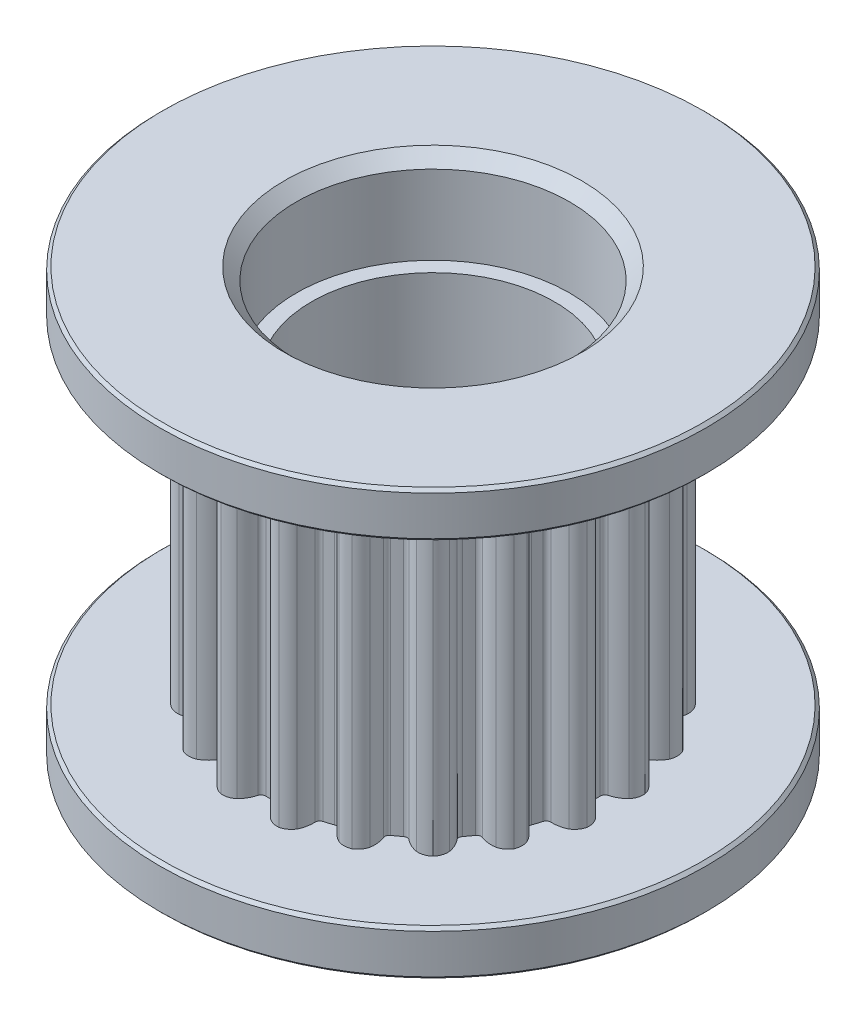
SolidWorks part; units mm, degrees
material "6061 Alloy"
ref_plane "Front Plane" through (0, 0, 0) normal (0, 0, 1) x (1, 0, 0)
ref_plane "Top Plane" through (0, 0, 0) normal (0, 1, 0) x (1, 0, 0)
ref_plane "Right Plane" through (0, 0, 0) normal (1, 0, 0) x (0, 0, -1)
sketch "Body Sketch" plane through (0, 0, 0) normal (0, 0, 1) x (1, 0, 0)
  line L0 (6.11, -5.5) -> (6.11, 5.5)
  line L1 (6.11, 5.5) -> (9, 5.5)
  line L2 (9, 5.5) -> (9, 7)
  line L3 (9, 7) -> (4.5, 7)
  line L4 (4.5, 7) -> (4.5, 4)
  line L5 (4.5, 4) -> (4, 4)
  line L6 (4, 4) -> (4, -4)
  line L7 (4, -4) -> (4.5, -4)
  line L8 (4.5, -4) -> (4.5, -7)
  line L9 (4.5, -7) -> (9, -7)
  line L10 (9, -7) -> (9, -5.5)
  line L11 (9, -5.5) -> (6.11, -5.5)
  line L12 (0, 0) -> (4, 0) construction
  line L13 (0, 7) -> (0, -7) construction
  dimension "BearingOD" = 9
  dimension "Height" = 14
  dimension "FlangeHeight" = 1.5
  dimension "BearingHeight" = 3
  dimension "BearingRestDiaControl" = 0.5
  dimension "RefBodyInnerDiameter" = 8
  dimension "FlangeDiaControl" = 4.5
  dimension "RefFlangeDia" = 18
  dimension "BeltPathDiaControl" = 1.61
  dimension "RefBeltPathDia" = 12.22
revolve "Body" add sketch "Body Sketch" angle 360 about L13
sketch "GT2 Profile Sketch" plane through (0, 0, 0) normal (0, 1, 0) x (1, 0, 0)
  line L1 (0, -6.11) -> (0, -5.36) construction
  line L2 (-0.9955, -6.0283) -> (-0.8733, -5.2884) construction
  line L3 (0, 0) -> (-0.8733, -5.2884) construction
  line L4 (0.9955, -6.0283) -> (0, 0) construction
  arc A3 (0.2997, -5.4688) -> (0.1507, -5.3579) centre (0.1549, -5.5078) ccw
  arc A4 (-0.9955, -6.0283) -> (0.9955, -6.0283) centre (0, 0) ccw
  arc A5 (-0.2997, -5.4688) -> (-0.1507, -5.3579) centre (-0.1549, -5.5078) cw
  arc A6 (-0.2997, -5.4688) -> (-0.5497, -5.907) centre (-1.2653, -5.2085) cw
  circle A7 centre (0, 0) radius 6.11 construction
  arc A8 (-0.1507, -5.3579) -> (0.1507, -5.3579) centre (0, 0) ccw
  arc A9 (-0.5497, -5.907) -> (-0.9955, -6.0283) centre (-0.9051, -5.4808) cw
  arc A10 (0.2997, -5.4688) -> (0.5497, -5.907) centre (1.2653, -5.2085) ccw
  arc A11 (0.5497, -5.907) -> (0.9955, -6.0283) centre (0.9051, -5.4808) ccw
  circle A12 centre (0, 0) radius 5.36 construction
  dimension "BottomRadius" = 0.15
  dimension "MidRadius" = 1
  dimension "TopRadius" = 0.555
  dimension "Height" = 0.75
  dimension "XDistMidRadius" = 0.4
  dimension "ArcLengthAngle" = 18.755
  dimension "ArcLength" = 2
sketch "Thru Bore Sketch" [suppressed] plane through (0, 0, 0) normal (0, 1, 0) x (1, 0, 0)
  circle A0 centre (0, 0) radius 4
  circle A2 centre (0, 0) radius 4 construction
extrude "Thru Bore" [suppressed] cut sketch "Thru Bore Sketch" against normal through all both and the other way through all
extrude "GT2 Profile" cut sketch "GT2 Profile Sketch" against normal up to surface and the other way up to surface up to face at (0, -5.5, 6.11) other way up to face at (0, 5.5, 9)
pattern_circular "GT2 Groove Circular Pattern" count 20 over 360 about axis through (0, 0, 0) along (0, 1, 0) of "GT2 Profile"
chamfer "Inner Chamfer" distance 0.4 angle 45 2 edges at (0, -7, 4.5) (0, 7, 4.5)
chamfer "Outer Chamfer" distance 0.1 angle 45 4 edges at (0, -7, 9) (0, -5.5, 9) (0, 5.5, 9) (0, 7, 9)
equation "\"NumTeeth@GT2 Groove Circular Pattern\"=int(360/\"ArcLengthAngle@GT2 Profile Sketch\")+1"
